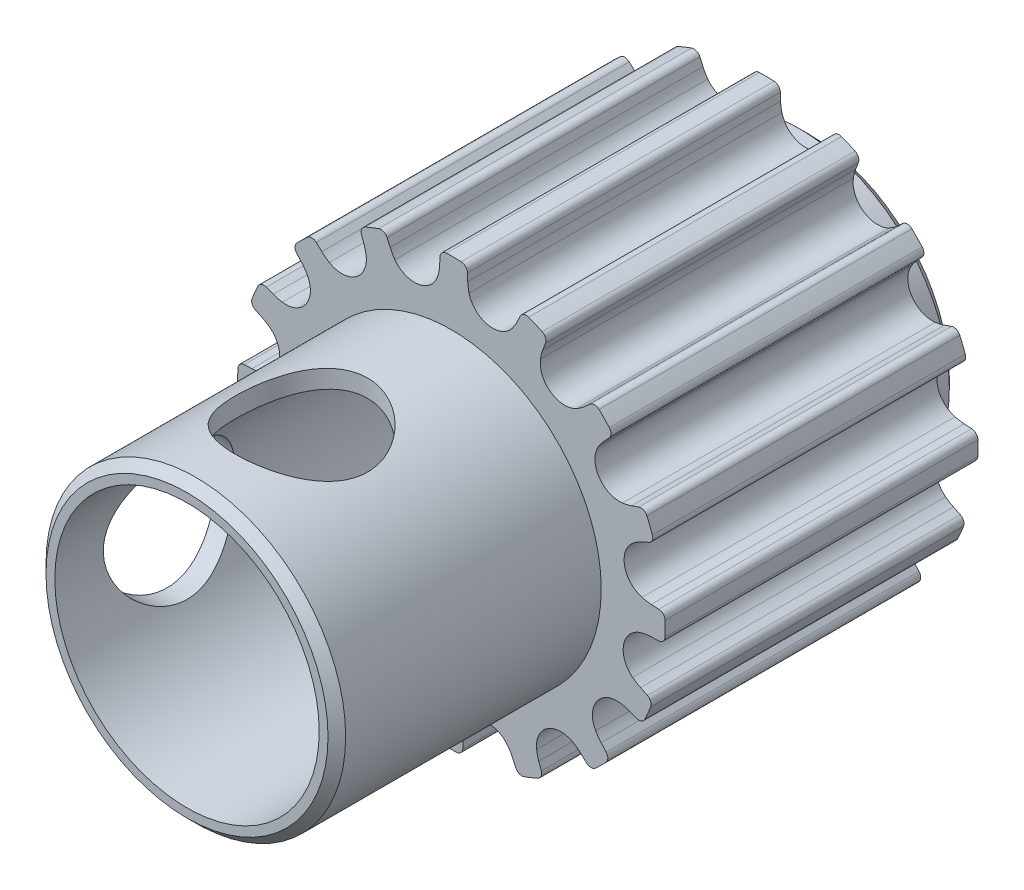
SolidWorks part; units mm, degrees
material "1060 Сплав"
ref_plane "Front Plane" through (0, 0, 0) normal (0, 0, 1) x (1, 0, 0)
ref_plane "Top Plane" through (0, 0, 0) normal (0, 1, 0) x (1, 0, 0)
ref_plane "Right Plane" through (0, 0, 0) normal (1, 0, 0) x (0, 0, -1)
sketch "Sketch1" plane through (0, 0, 0) normal (0, 0, 1) x (1, 0, 0)
  circle A0 centre (0, 0) radius 3.4
  dimension "D1" = 6.8
extrude "Extrude1" add sketch "Sketch1" along normal blind 1
sketch "Sketch2" plane through (0, 0, 1) normal (0, 0, 1) x (1, 0, 0)
  circle A0 centre (0, 0) radius 4.9
  dimension "D1" = 9.8
extrude "Extrude2" add sketch "Sketch2" along normal blind 7.1
sketch "Sketch3" plane through (0, 0, 8.1) normal (0, 0, 1) x (1, 0, 0)
  circle A0 centre (0, 0) radius 3.4
  dimension "D1" = 6.8
extrude "Extrude3" add sketch "Sketch3" along normal blind 6
sketch "Sketch4" plane through (0, 0, 14.1) normal (0, 0, 1) x (1, 0, 0)
  circle A0 centre (0, 0) radius 3
  dimension "D1" = 6
extrude "Extrude4" cut sketch "Sketch4" against normal through all
sketch "Sketch5" plane through (0, 0, 8.1) normal (0, 0, 1) x (1, 0, 0)
  line L0 (0, 0) -> (0, 4.85) construction
  line L1 (0, 4.85) -> (1.957, 4.4376) construction
  line L2 (1.957, 4.4376) -> (0, 0) construction
  line L3 (0.9785, 4.6438) -> (0, 0) construction
  line L4 (0.9785, 4.6438) -> (0.9383, 4.453) construction
  line L5 (0.9785, 4.6438) -> (1.3699, 4.5613) construction
  line L6 (0.3705, 4.5279) -> (0.3647, 4.7001) construction
  line L7 (1.4881, 4.2924) -> (1.5628, 4.4476)
  line L8 (2.075, 4.0414) -> (2.1356, 4.2028)
  line L9 (3.0174, 3.3962) -> (3.1459, 3.511)
  line L10 (3.4636, 2.9397) -> (3.5814, 3.0656)
  line L11 (4.0874, 1.9829) -> (4.2501, 2.0399)
  line L12 (4.325, 1.3905) -> (4.4819, 1.4617)
  line L13 (4.5351, 0.2678) -> (4.7072, 0.2582)
  line L14 (4.5279, -0.3705) -> (4.7001, -0.3647)
  line L15 (4.2924, -1.4881) -> (4.4476, -1.5628)
  line L16 (4.0414, -2.075) -> (4.2028, -2.1356)
  line L17 (3.3962, -3.0174) -> (3.511, -3.1459)
  line L18 (2.9397, -3.4636) -> (3.0656, -3.5814)
  line L19 (1.9829, -4.0874) -> (2.0399, -4.2501)
  line L20 (1.3905, -4.325) -> (1.4617, -4.4819)
  line L21 (0.2678, -4.5351) -> (0.2582, -4.7072)
  line L22 (-0.3705, -4.5279) -> (-0.3647, -4.7001)
  line L23 (-1.4881, -4.2924) -> (-1.5628, -4.4476)
  line L24 (-2.075, -4.0414) -> (-2.1356, -4.2028)
  line L25 (-3.0174, -3.3962) -> (-3.1459, -3.511)
  line L26 (-3.4636, -2.9397) -> (-3.5814, -3.0656)
  line L27 (-4.0874, -1.9829) -> (-4.2501, -2.0399)
  line L28 (-4.325, -1.3905) -> (-4.4819, -1.4617)
  line L29 (-4.5351, -0.2678) -> (-4.7072, -0.2582)
  line L30 (-4.5279, 0.3705) -> (-4.7001, 0.3647)
  line L31 (-4.2924, 1.4881) -> (-4.4476, 1.5628)
  line L32 (-4.0414, 2.075) -> (-4.2028, 2.1356)
  line L33 (-3.3962, 3.0174) -> (-3.511, 3.1459)
  line L34 (-2.9397, 3.4636) -> (-3.0656, 3.5814)
  line L35 (-1.9829, 4.0874) -> (-2.0399, 4.2501)
  line L36 (-1.3905, 4.325) -> (-1.4617, 4.4819)
  line L37 (-0.2678, 4.5279) -> (-0.2584, 4.6999)
  line L38 (0.3647, 4.7001) -> (0.3705, 4.5279)
  circle A0 centre (0, 0) radius 4.85 construction
  arc A1 (0.4, 4.3179) -> (1.3763, 4.1122) centre (0.9383, 4.453) ccw
  arc A2 (0, 4.85) -> (0.2216, 4.8449) centre (0, 0) cw construction
  arc A3 (0.3705, 4.5279) -> (0.4, 4.3179) centre (1.3699, 4.5613) ccw
  arc A4 (0.2216, 4.8449) -> (0.3647, 4.7001) centre (0.2148, 4.6951) cw
  arc A5 (1.4881, 4.2924) -> (1.3763, 4.1122) centre (0.5871, 4.7263) cw
  arc A6 (1.7522, 4.5224) -> (1.5628, 4.4476) centre (1.698, 4.3826) ccw
  arc A7 (1.957, 4.4376) -> (1.7522, 4.5224) centre (0, 0) ccw construction
  arc A8 (2.0589, 4.3913) -> (2.1356, 4.2028) centre (1.9952, 4.2555) cw
  arc A9 (2.075, 4.0414) -> (2.0219, 3.8361) centre (3.0112, 3.6899) ccw
  arc A10 (2.0219, 3.8361) -> (2.8452, 3.2725) centre (2.571, 3.755) ccw
  arc A11 (3.0174, 3.3962) -> (2.8452, 3.2725) centre (2.3511, 4.1418) cw
  arc A12 (3.3495, 3.5076) -> (3.1459, 3.511) centre (3.2459, 3.3992) ccw
  arc A13 (3.5826, 3.2692) -> (3.5814, 3.0656) centre (3.4718, 3.168) cw
  arc A14 (3.4636, 2.9397) -> (3.3361, 2.7704) centre (4.194, 2.2567) ccw
  arc A15 (3.3361, 2.7704) -> (3.8809, 1.9345) centre (3.8122, 2.4853) ccw
  arc A16 (4.0874, 1.9829) -> (3.8809, 1.9345) centre (3.7571, 2.9268) cw
  arc A17 (4.4368, 1.9589) -> (4.2501, 2.0399) centre (4.2996, 1.8983) ccw
  arc A18 (4.561, 1.6493) -> (4.4819, 1.4617) centre (4.4199, 1.5983) cw
  arc A19 (4.325, 1.3905) -> (4.1423, 1.2828) centre (4.7384, 0.4799) ccw
  arc A20 (4.1423, 1.2828) -> (4.3258, 0.3021) centre (4.4731, 0.8372) ccw
  arc A21 (4.5351, 0.2678) -> (4.3258, 0.3021) centre (4.5912, 1.2663) cw
  arc A22 (4.8487, 0.1119) -> (4.7072, 0.2582) centre (4.6987, 0.1084) ccw
  arc A23 (4.8449, -0.2216) -> (4.7001, -0.3647) centre (4.6951, -0.2148) cw
  arc A24 (4.5279, -0.3705) -> (4.3179, -0.4) centre (4.5613, -1.3699) ccw
  arc A25 (4.3179, -0.4) -> (4.1122, -1.3763) centre (4.453, -0.9383) ccw
  arc A26 (4.2924, -1.4881) -> (4.1122, -1.3763) centre (4.7263, -0.5871) cw
  arc A27 (4.5224, -1.7522) -> (4.4476, -1.5628) centre (4.3826, -1.698) ccw
  arc A28 (4.3913, -2.0589) -> (4.2028, -2.1356) centre (4.2555, -1.9952) cw
  arc A29 (4.0414, -2.075) -> (3.8361, -2.0219) centre (3.6899, -3.0112) ccw
  arc A30 (3.8361, -2.0219) -> (3.2725, -2.8452) centre (3.755, -2.571) ccw
  arc A31 (3.3962, -3.0174) -> (3.2725, -2.8452) centre (4.1418, -2.3511) cw
  arc A32 (3.5076, -3.3495) -> (3.511, -3.1459) centre (3.3992, -3.2459) ccw
  arc A33 (3.2692, -3.5826) -> (3.0656, -3.5814) centre (3.168, -3.4718) cw
  arc A34 (2.9397, -3.4636) -> (2.7704, -3.3361) centre (2.2567, -4.194) ccw
  arc A35 (2.7704, -3.3361) -> (1.9345, -3.8809) centre (2.4853, -3.8122) ccw
  arc A36 (1.9829, -4.0874) -> (1.9345, -3.8809) centre (2.9268, -3.7571) cw
  arc A37 (1.9589, -4.4368) -> (2.0399, -4.2501) centre (1.8983, -4.2996) ccw
  arc A38 (1.6493, -4.561) -> (1.4617, -4.4819) centre (1.5983, -4.4199) cw
  arc A39 (1.3905, -4.325) -> (1.2828, -4.1423) centre (0.4799, -4.7384) ccw
  arc A40 (1.2828, -4.1423) -> (0.3021, -4.3258) centre (0.8372, -4.4731) ccw
  arc A41 (0.2678, -4.5351) -> (0.3021, -4.3258) centre (1.2663, -4.5912) cw
  arc A42 (0.1119, -4.8487) -> (0.2582, -4.7072) centre (0.1084, -4.6987) ccw
  arc A43 (-0.2216, -4.8449) -> (-0.3647, -4.7001) centre (-0.2148, -4.6951) cw
  arc A44 (-0.3705, -4.5279) -> (-0.4, -4.3179) centre (-1.3699, -4.5613) ccw
  arc A45 (-0.4, -4.3179) -> (-1.3763, -4.1122) centre (-0.9383, -4.453) ccw
  arc A46 (-1.4881, -4.2924) -> (-1.3763, -4.1122) centre (-0.5871, -4.7263) cw
  arc A47 (-1.7522, -4.5224) -> (-1.5628, -4.4476) centre (-1.698, -4.3826) ccw
  arc A48 (-2.0589, -4.3913) -> (-2.1356, -4.2028) centre (-1.9952, -4.2555) cw
  arc A49 (-2.075, -4.0414) -> (-2.0219, -3.8361) centre (-3.0112, -3.6899) ccw
  arc A50 (-2.0219, -3.8361) -> (-2.8452, -3.2725) centre (-2.571, -3.755) ccw
  arc A51 (-3.0174, -3.3962) -> (-2.8452, -3.2725) centre (-2.3511, -4.1418) cw
  arc A52 (-3.3495, -3.5076) -> (-3.1459, -3.511) centre (-3.2459, -3.3992) ccw
  arc A53 (-3.5826, -3.2692) -> (-3.5814, -3.0656) centre (-3.4718, -3.168) cw
  arc A54 (-3.4636, -2.9397) -> (-3.3361, -2.7704) centre (-4.194, -2.2567) ccw
  arc A55 (-3.3361, -2.7704) -> (-3.8809, -1.9345) centre (-3.8122, -2.4853) ccw
  arc A56 (-4.0874, -1.9829) -> (-3.8809, -1.9345) centre (-3.7571, -2.9268) cw
  arc A57 (-4.4368, -1.9589) -> (-4.2501, -2.0399) centre (-4.2996, -1.8983) ccw
  arc A58 (-4.561, -1.6493) -> (-4.4819, -1.4617) centre (-4.4199, -1.5983) cw
  arc A59 (-4.325, -1.3905) -> (-4.1423, -1.2828) centre (-4.7384, -0.4799) ccw
  arc A60 (-4.1423, -1.2828) -> (-4.3258, -0.3021) centre (-4.4731, -0.8372) ccw
  arc A61 (-4.5351, -0.2678) -> (-4.3258, -0.3021) centre (-4.5912, -1.2663) cw
  arc A62 (-4.8487, -0.1119) -> (-4.7072, -0.2582) centre (-4.6987, -0.1084) ccw
  arc A63 (-4.8449, 0.2216) -> (-4.7001, 0.3647) centre (-4.6951, 0.2148) cw
  arc A64 (-4.5279, 0.3705) -> (-4.3179, 0.4) centre (-4.5613, 1.3699) ccw
  arc A65 (-4.3179, 0.4) -> (-4.1122, 1.3763) centre (-4.453, 0.9383) ccw
  arc A66 (-4.2924, 1.4881) -> (-4.1122, 1.3763) centre (-4.7263, 0.5871) cw
  arc A67 (-4.5224, 1.7522) -> (-4.4476, 1.5628) centre (-4.3826, 1.698) ccw
  arc A68 (-4.3913, 2.0589) -> (-4.2028, 2.1356) centre (-4.2555, 1.9952) cw
  arc A69 (-4.0414, 2.075) -> (-3.8361, 2.0219) centre (-3.6899, 3.0112) ccw
  arc A70 (-3.8361, 2.0219) -> (-3.2725, 2.8452) centre (-3.755, 2.571) ccw
  arc A71 (-3.3962, 3.0174) -> (-3.2725, 2.8452) centre (-4.1418, 2.3511) cw
  arc A72 (-3.5076, 3.3495) -> (-3.511, 3.1459) centre (-3.3992, 3.2459) ccw
  arc A73 (-3.2692, 3.5826) -> (-3.0656, 3.5814) centre (-3.168, 3.4718) cw
  arc A74 (-2.9397, 3.4636) -> (-2.7704, 3.3361) centre (-2.2567, 4.194) ccw
  arc A75 (-2.7704, 3.3361) -> (-1.9345, 3.8809) centre (-2.4853, 3.8122) ccw
  arc A76 (-1.9829, 4.0874) -> (-1.9345, 3.8809) centre (-2.9268, 3.7571) cw
  arc A77 (-1.9589, 4.4368) -> (-2.0399, 4.2501) centre (-1.8983, 4.2996) ccw
  arc A78 (-1.6493, 4.561) -> (-1.4617, 4.4819) centre (-1.5983, 4.4199) cw
  arc A79 (-1.3905, 4.325) -> (-1.2828, 4.1351) centre (-0.4718, 4.7201) ccw
  arc A80 (-1.2828, 4.1351) -> (-0.3021, 4.3186) centre (-0.8372, 4.4659) ccw
  arc A81 (-0.2678, 4.5279) -> (-0.3021, 4.3186) centre (-1.2663, 4.584) cw
  arc A82 (-0.1119, 4.8487) -> (-0.2584, 4.6999) centre (-0.1084, 4.6987) ccw
  arc A83 (-0.1119, 4.8487) -> (0.2216, 4.8449) centre (0, 0) cw
  arc A84 (1.7522, 4.5224) -> (2.0589, 4.3913) centre (0, 0) cw
  arc A85 (3.3495, 3.5076) -> (3.5826, 3.2692) centre (0, 0) cw
  arc A86 (4.4368, 1.9589) -> (4.561, 1.6493) centre (0, 0) cw
  arc A87 (4.8487, 0.1119) -> (4.8449, -0.2216) centre (0, 0) cw
  arc A88 (4.5224, -1.7522) -> (4.3913, -2.0589) centre (0, 0) cw
  arc A89 (3.5076, -3.3495) -> (3.2692, -3.5826) centre (0, 0) cw
  arc A90 (1.9589, -4.4368) -> (1.6493, -4.561) centre (0, 0) cw
  arc A91 (0.1119, -4.8487) -> (-0.2216, -4.8449) centre (0, 0) cw
  arc A92 (-1.7522, -4.5224) -> (-2.0589, -4.3913) centre (0, 0) cw
  arc A93 (-3.3495, -3.5076) -> (-3.5826, -3.2692) centre (0, 0) cw
  arc A94 (-4.4368, -1.9589) -> (-4.561, -1.6493) centre (0, 0) cw
  arc A95 (-4.8487, -0.1119) -> (-4.8449, 0.2216) centre (0, 0) cw
  arc A96 (-4.5224, 1.7522) -> (-4.3913, 2.0589) centre (0, 0) cw
  arc A97 (-3.5076, 3.3495) -> (-3.2692, 3.5826) centre (0, 0) cw
  arc A98 (-1.9589, 4.4368) -> (-1.6493, 4.561) centre (0, 0) cw
  point P15 (0.3601, 4.8366)
  point P22 (0, 0)
  point P219 (0, 0)
  point P251 (0, 0)
  dimension "D1" = 9.7
  dimension "D3" = 0.555
  dimension "D4" = 1
  dimension "D5" = 0.4
  dimension "D6" = 0.15
  dimension "D8" = 16
  dimension "D2" = 2
  dimension "D7" = 0.1724
extrude "Extrude5" cut sketch "Sketch5" against normal through all flip side to cut
sketch "Sketch6" plane through (0, 0, 0) normal (0, 1, 0) x (1, 0, 0)
  line L0 (0, -14.1) -> (0, -8.1) construction
  line L1 (-3.4, -14.1) -> (3.4, -14.1) construction
  line L2 (-3.4, -8.1) -> (3.4, -8.1) construction
  circle A0 centre (0, -11.5) radius 1.5
  dimension "D1" = 3
  dimension "D2" = 2.6
extrude "Extrude6" cut sketch "Sketch6" along normal through all
pattern_circular "CirPattern1" count 2 over 90 about axis through (0, 0, 14.1) along (0, 0, -1) of "Extrude6"
chamfer "Chamfer1" distance 0.2 angle 45 2 edges at (3.4, 0, 14.1) (3.4, 0, 0)
equation "\"2б6\"=2.16585"
